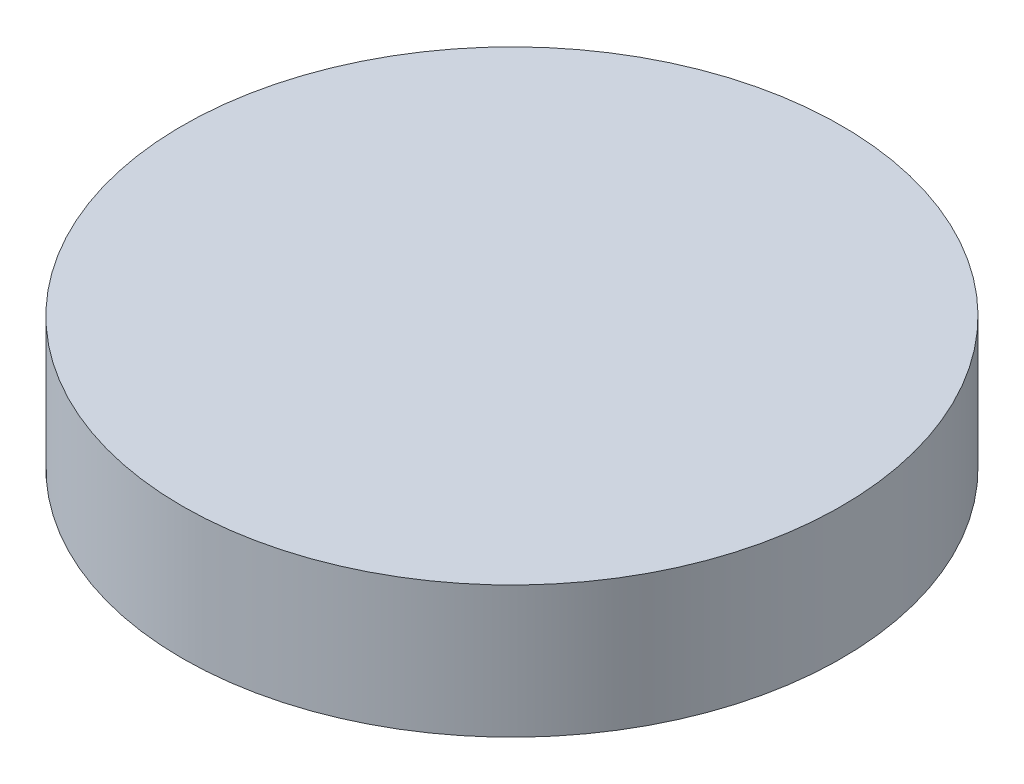
SolidWorks part; units mm, degrees
ref_plane "Front Plane" through (0, 0, 0) normal (0, 0, 1) x (1, 0, 0)
ref_plane "Top Plane" through (0, 0, 0) normal (0, 1, 0) x (1, 0, 0)
ref_plane "Right Plane" through (0, 0, 0) normal (1, 0, 0) x (0, 0, -1)
other "Configuration Table"
sketch "Sketch1" plane through (0, 0, 0) normal (0, 1, 0) x (1, 0, 0)
  circle A0 centre (0, 360) radius 30
extrude "KAPYAG_dolum_agzi_D60" add sketch "Sketch1" along normal blind 12 from offset 260 separate body
